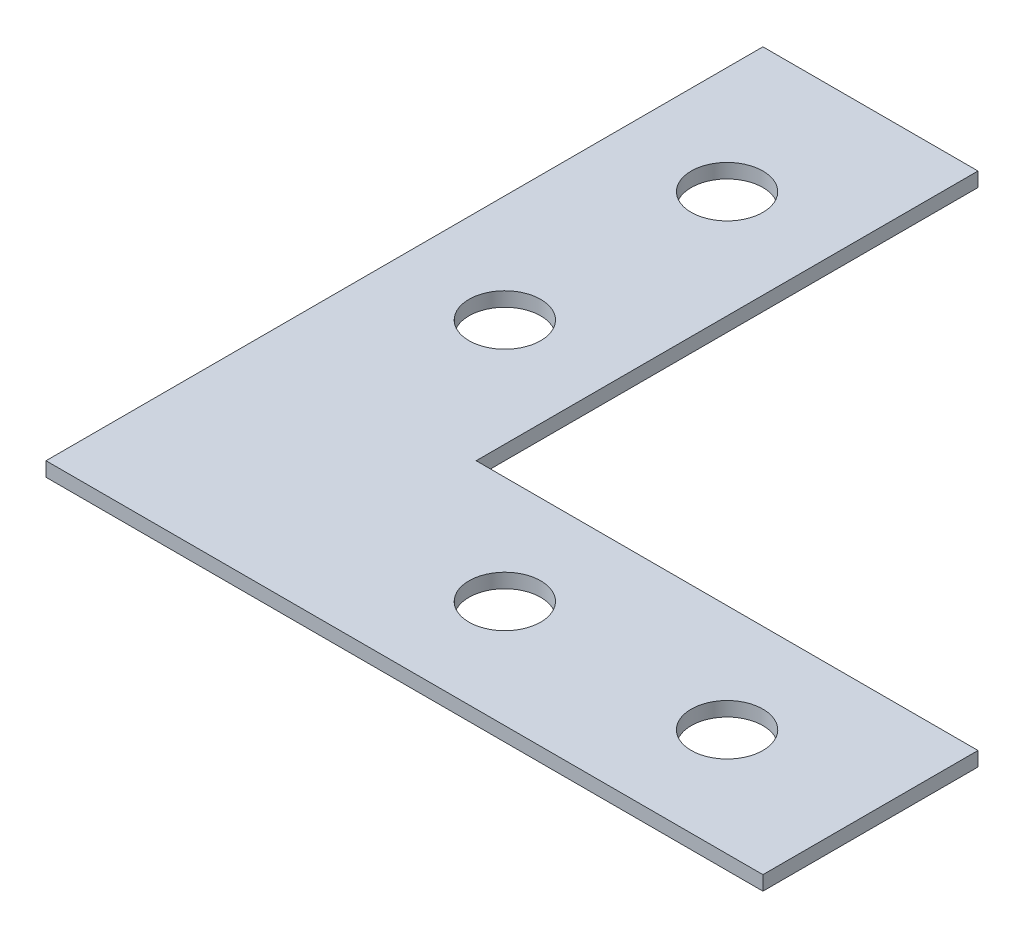
SolidWorks part; units mm, degrees
ref_plane "Front Plane" through (0, 0, 0) normal (0, 0, 1) x (1, 0, 0)
ref_plane "Top Plane" through (0, 0, 0) normal (0, 1, 0) x (1, 0, 0)
ref_plane "Right Plane" through (0, 0, 0) normal (1, 0, 0) x (0, 0, -1)
sketch "Sketch2" plane through (0, 0, 0) normal (0, 1, 0) x (1, 0, 0)
  line L0 (0, 0) -> (0, 50)
  line L1 (0, 50) -> (15, 50)
  line L2 (15, 50) -> (15, 15)
  line L3 (15, 15) -> (50, 15)
  line L4 (50, 15) -> (50, 0)
  line L5 (50, 0) -> (0, 0)
  dimension "D1" = 15
  dimension "D2" = 50
extrude "Boss-Extrude1" add sketch "Sketch2" along normal blind 1
sketch "Sketch4" plane through (0, 1, 0) normal (0, 1, 0) x (1, 0, 0)
  line L0 (0, 0) -> (50, 0) construction
  line L1 (15, 15) -> (0, 0)
  circle A0 centre (7.5, 24.5) radius 2.5
  circle A1 centre (7.5, 40) radius 2.5
  circle A2 centre (24.5, 7.5) radius 2.5
  circle A3 centre (40, 7.5) radius 2.5
  dimension "D2" = 5
  dimension "D3" = 7.5
  dimension "D4" = 24.5
  dimension "D5" = 15.5
extrude "Cut-Extrude1" cut sketch "Sketch4" against normal through all contours A1 | A0 | A2 | A3
